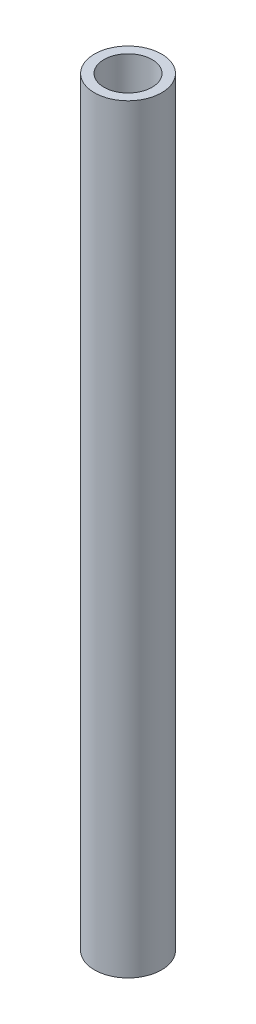
SolidWorks part; units mm, degrees
ref_plane "Front Plane" through (0, 0, 0) normal (0, 0, 1) x (1, 0, 0)
ref_plane "Top Plane" through (0, 0, 0) normal (0, 1, 0) x (1, 0, 0)
ref_plane "Right Plane" through (0, 0, 0) normal (1, 0, 0) x (0, 0, -1)
sketch "Sketch1" plane through (0, 0, 0) normal (0, 1, 0) x (1, 0, 0)
  circle A0 centre (0, 0) radius 7.6454
  circle A1 centre (0, 0) radius 10.668
  dimension "D1" = 21.336
  dimension "D2" = 15.2908
extrude "Boss-Extrude1" add sketch "Sketch1" along normal blind 241.3
ref_plane "Plane1" through (0, 120.65, 0) normal (0, 1, 0) x (1, 0, 0)
ref_plane "Plane2" through (0, 120.65, 0) normal (0, -1, 0) x (-1, 0, 0)
